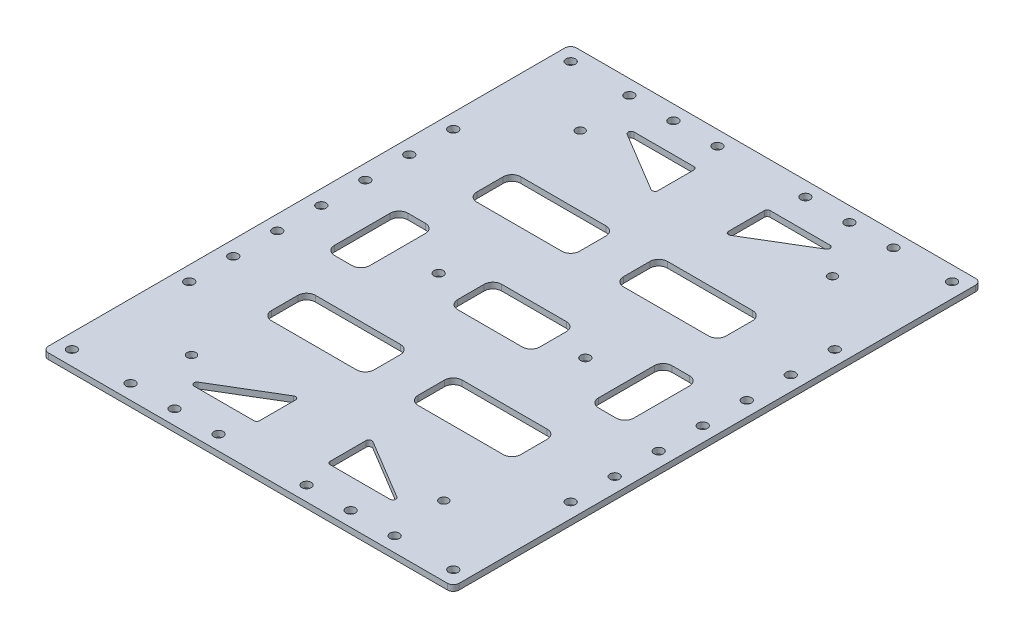
SolidWorks part; units mm, degrees
material "Thornel Mat VMA"
ref_plane "前视基准面" through (0, 0, 0) normal (0, 0, 1) x (1, 0, 0)
ref_plane "上视基准面" through (0, 0, 0) normal (0, 1, 0) x (1, 0, 0)
ref_plane "右视基准面" through (0, 0, 0) normal (1, 0, 0) x (0, 0, -1)
other "Configuration Table"
sketch "草图1" plane through (0, 0, 0) normal (0, 1, 0) x (1, 0, 0)
  line L1 (-90, -90) -> (90, -90)
  line L2 (-90, -90) -> (-90, 90)
  line L3 (-90, 90) -> (90, 90)
  line L4 (90, -90) -> (90, 90)
  line L5 (-90, -90) -> (90, 90) construction
  line L6 (-90, 90) -> (90, -90) construction
  point P0 (0, 0)
  dimension "D1" = 180
  dimension "D2" = 180
extrude "凸台-拉伸1" add sketch "草图1" along normal blind 2
sketch "草图2" plane through (0, 2, 0) normal (0, 1, 0) x (1, 0, 0)
  line L1 (-42.9895, -66.2305) -> (42.9895, -66.2305) construction
  line L2 (-42.9895, -66.2305) -> (-42.9895, 66.2305) construction
  line L3 (-42.9895, 66.2305) -> (42.9895, 66.2305) construction
  line L4 (42.9895, -66.2305) -> (42.9895, 66.2305) construction
  line L5 (-42.9895, -66.2305) -> (42.9895, 66.2305) construction
  line L6 (-42.9895, 66.2305) -> (42.9895, -66.2305) construction
  circle A0 centre (-42.9895, 66.2305) radius 1.5
  circle A1 centre (42.9895, 66.2305) radius 1.5
  circle A2 centre (-42.9895, -66.2305) radius 1.5
  circle A3 centre (42.9895, -66.2305) radius 1.5
  point P0 (0, 0)
  dimension "D3" = 3
  dimension "D1" = 132.461
  dimension "D2" = 85.979
extrude "切除-拉伸1" cut sketch "草图2" against normal blind 3
sketch "草图3" plane through (0, 2, 0) normal (0, 1, 0) x (1, 0, 0)
  line L0 (-90, 0) -> (90, 0) construction
  line L1 (-14, -7.5) -> (14, -7.5)
  line L2 (-14, -7.5) -> (-14, 7.5)
  line L3 (-14, 7.5) -> (14, 7.5)
  line L4 (14, -7.5) -> (14, 7.5)
  line L5 (-14, -7.5) -> (14, 7.5) construction
  line L6 (-14, 7.5) -> (14, -7.5) construction
  line L7 (-90, 90) -> (-90, -90) construction
  line L8 (90, -90) -> (90, 90) construction
  line L9 (0, 90) -> (0, -90) construction
  line L10 (90, 90) -> (-90, 90) construction
  line L11 (-90, -90) -> (90, -90) construction
  line L12 (-25, 35) -> (0, 35) construction
  line L13 (-42.5, 27.5) -> (-7.5, 27.5)
  line L14 (-42.5, 27.5) -> (-42.5, 42.5)
  line L15 (-42.5, 42.5) -> (-7.5, 42.5)
  line L16 (-7.5, 27.5) -> (-7.5, 42.5)
  line L17 (-42.5, 27.5) -> (-7.5, 42.5) construction
  line L18 (-42.5, 42.5) -> (-7.5, 27.5) construction
  line L23 (42.5, 42.5) -> (7.5, 42.5)
  line L24 (7.5, 27.5) -> (7.5, 42.5)
  line L25 (-25, 35) -> (-25, 0) construction
  line L26 (42.5, 27.5) -> (7.5, 27.5)
  line L27 (42.5, 27.5) -> (42.5, 42.5)
  line L28 (51, 12.5) -> (39, 12.5)
  line L29 (-51, -12.5) -> (-39, -12.5)
  line L30 (-51, -12.5) -> (-51, 12.5)
  line L31 (-51, 12.5) -> (-39, 12.5)
  line L32 (-39, -12.5) -> (-39, 12.5)
  line L33 (-51, -12.5) -> (-39, 12.5) construction
  line L34 (-51, 12.5) -> (-39, -12.5) construction
  line L35 (51, -12.5) -> (39, -12.5)
  line L36 (51, -12.5) -> (51, 12.5)
  line L37 (39, -12.5) -> (39, 12.5)
  line L38 (-42.5, -42.5) -> (-7.5, -42.5)
  line L39 (-7.5, -27.5) -> (-7.5, -42.5)
  line L40 (-42.5, -27.5) -> (-7.5, -27.5)
  line L41 (-42.5, -27.5) -> (-42.5, -42.5)
  line L42 (42.5, -27.5) -> (42.5, -42.5)
  line L43 (42.5, -27.5) -> (7.5, -27.5)
  line L44 (7.5, -27.5) -> (7.5, -42.5)
  line L45 (42.5, -42.5) -> (7.5, -42.5)
  line L51 (-37, 75) -> (-12, 75)
  line L52 (-12, 75) -> (-12, 60)
  line L56 (-12, 60) -> (-37, 75)
  line L57 (12, 75) -> (12, 60)
  line L58 (37, 75) -> (12, 75)
  line L59 (12, 60) -> (37, 75)
  line L60 (37, -75) -> (12, -75)
  line L61 (12, -60) -> (37, -75)
  line L62 (12, -75) -> (12, -60)
  line L63 (-12, -75) -> (-12, -60)
  line L64 (-37, -75) -> (-12, -75)
  line L65 (-12, -60) -> (-37, -75)
  point P0 (0, 0)
  point P18 (-25, 35)
  point P27 (-45, 0)
  dimension "D1" = 28
  dimension "D2" = 15
  dimension "D3" = 35
  dimension "D4" = 25
  dimension "D5" = 35
  dimension "D6" = 15
  dimension "D7" = 45
  dimension "D8" = 12
  dimension "D9" = 25
  dimension "D10" = 15
  dimension "D11" = 15
  dimension "D12" = 12
  dimension "D13" = 25
extrude "切除-拉伸2" cut sketch "草图3" against normal blind 3
fillet "圆角1" radius 3 4 edges at (-14, 1, 7.5) (14, 1, 7.5) (14, 1, -7.5) (-14, 1, -7.5)
sketch "草图5" plane through (0, 2, 0) normal (0, 1, 0) x (1, 0, 0)
  line L0 (80, 90) -> (90, 80)
  line L1 (-77.5, -77.5) -> (77.5, -77.5) construction
  line L2 (-77.5, -77.5) -> (-77.5, 77.5) construction
  line L3 (-77.5, 77.5) -> (77.5, 77.5) construction
  line L4 (77.5, -77.5) -> (77.5, 77.5) construction
  line L5 (-77.5, -77.5) -> (77.5, 77.5) construction
  line L6 (-77.5, 77.5) -> (77.5, -77.5) construction
  line L7 (69.0147, 77.5) -> (77.5, 69.0147) construction
  line L8 (69.0147, 77.5) -> (77.5, 85.9853) construction
  line L9 (77.5, 85.9853) -> (85.9853, 77.5) construction
  line L10 (77.5, 69.0147) -> (85.9853, 77.5) construction
  line L11 (69.0147, 77.5) -> (85.9853, 77.5) construction
  line L12 (77.5, 85.9853) -> (77.5, 69.0147) construction
  line L13 (90, 90) -> (-90, 90) construction
  line L14 (90, -90) -> (90, 90) construction
  line L24 (90, 80) -> (90, 90)
  line L25 (90, 90) -> (80, 90)
  line L26 (0, 90) -> (0, -90) construction
  line L27 (-90, -90) -> (90, -90) construction
  line L28 (90, 0) -> (-90, 0) construction
  line L29 (-90, 90) -> (-90, -90) construction
  line L30 (-77.5, 85.9853) -> (-77.5, 69.0147) construction
  line L31 (-69.0147, 77.5) -> (-85.9853, 77.5) construction
  line L32 (-77.5, 69.0147) -> (-85.9853, 77.5) construction
  line L33 (-77.5, 85.9853) -> (-85.9853, 77.5) construction
  line L34 (-69.0147, 77.5) -> (-77.5, 85.9853) construction
  line L35 (-69.0147, 77.5) -> (-77.5, 69.0147) construction
  line L36 (-90, 90) -> (-80, 90)
  line L37 (-90, 80) -> (-90, 90)
  line L38 (-80, 90) -> (-90, 80)
  line L39 (-69.0147, -77.5) -> (-77.5, -69.0147) construction
  line L40 (-69.0147, -77.5) -> (-77.5, -85.9853) construction
  line L41 (-77.5, -85.9853) -> (-85.9853, -77.5) construction
  line L42 (-77.5, -69.0147) -> (-85.9853, -77.5) construction
  line L43 (-69.0147, -77.5) -> (-85.9853, -77.5) construction
  line L44 (-77.5, -85.9853) -> (-77.5, -69.0147) construction
  line L45 (77.5, -85.9853) -> (77.5, -69.0147) construction
  line L46 (69.0147, -77.5) -> (85.9853, -77.5) construction
  line L47 (77.5, -69.0147) -> (85.9853, -77.5) construction
  line L48 (77.5, -85.9853) -> (85.9853, -77.5) construction
  line L49 (69.0147, -77.5) -> (77.5, -85.9853) construction
  line L50 (69.0147, -77.5) -> (77.5, -69.0147) construction
  line L51 (-80, -90) -> (-90, -80)
  line L52 (-90, -80) -> (-90, -90)
  line L53 (-90, -90) -> (-80, -90)
  line L54 (90, -90) -> (80, -90)
  line L55 (90, -80) -> (90, -90)
  line L56 (80, -90) -> (90, -80)
  circle A0 centre (69.0147, 77.5) radius 1.7 construction
  circle A1 centre (77.5, 69.0147) radius 1.7
  circle A2 centre (77.5, 85.9853) radius 1.7
  circle A3 centre (85.9853, 77.5) radius 1.7
  circle A4 centre (-85.9853, 77.5) radius 1.7
  circle A5 centre (-77.5, 85.9853) radius 1.7
  circle A6 centre (-77.5, 69.0147) radius 1.7 construction
  circle A7 centre (-69.0147, 77.5) radius 1.7 construction
  circle A8 centre (-69.0147, -77.5) radius 1.7 construction
  circle A9 centre (-77.5, -69.0147) radius 1.7 construction
  circle A10 centre (-77.5, -85.9853) radius 1.7
  circle A11 centre (-85.9853, -77.5) radius 1.7
  circle A12 centre (85.9853, -77.5) radius 1.7
  circle A13 centre (77.5, -85.9853) radius 1.7
  circle A14 centre (77.5, -69.0147) radius 1.7 construction
  circle A15 centre (69.0147, -77.5) radius 1.7 construction
  point P0 (0, 0)
  dimension "D3" = 3.4
  dimension "D1" = 12
  dimension "D2" = 12
  dimension "D4" = 155
  dimension "D5" = 10
  dimension "D6" = 10
extrude "切除-拉伸3" cut sketch "草图5" against normal through all
sketch "草图6" plane through (0, 2, 0) normal (0, 1, 0) x (1, 0, 0)
  line L0 (90, 70) -> (70, 50)
  line L1 (90, -80) -> (90, 80) construction
  line L2 (70, 50) -> (70, -50)
  line L3 (70, -50) -> (90, -70)
  line L4 (90, -70) -> (90, 70)
  line L5 (-90, 0) -> (90, 0) construction
  line L6 (-90, 80) -> (-90, -80) construction
  line L7 (0, 90) -> (0, -90) construction
  line L8 (80, 90) -> (-80, 90) construction
  line L9 (-80, -90) -> (80, -90) construction
  line L10 (-70, -50) -> (-90, -70)
  line L11 (-70, 50) -> (-70, -50)
  line L12 (-90, 70) -> (-70, 50)
  line L13 (-90, -70) -> (-90, 70)
  dimension "D1" = 140
  dimension "D2" = 20
  dimension "D3" = 20
  dimension "D4" = 20
extrude "切除-拉伸4" cut sketch "草图6" against normal blind 10
sketch "草图7" plane through (0, 0, 0) normal (0, -1, 0) x (1, 0, 0)
  line L0 (-70, 0) -> (70, 0) construction
  line L1 (-70, -50) -> (-70, 50) construction
  line L2 (70, 50) -> (70, -50) construction
  line L3 (0, 90) -> (0, -90) construction
  line L4 (-80, 90) -> (80, 90) construction
  line L5 (80, -90) -> (-80, -90) construction
  line L6 (-65, -15) -> (-65, 15) construction
  line L7 (-65, 15) -> (-65, 30) construction
  line L8 (-65, 30) -> (-65, 45) construction
  line L9 (0, 85) -> (-15, 85) construction
  line L10 (-15, 85) -> (-30, 85) construction
  line L11 (-30, 85) -> (-45, 85) construction
  line L12 (30, 85) -> (45, 85) construction
  line L13 (15, 85) -> (30, 85) construction
  line L14 (-65, -30) -> (-65, -45) construction
  line L15 (-65, -15) -> (-65, -30) construction
  line L16 (65, -15) -> (65, -30) construction
  line L17 (65, -30) -> (65, -45) construction
  line L18 (65, 30) -> (65, 45) construction
  line L19 (65, 15) -> (65, 30) construction
  line L20 (65, -15) -> (65, 15) construction
  line L21 (15, -85) -> (30, -85) construction
  line L22 (30, -85) -> (45, -85) construction
  line L23 (-30, -85) -> (-45, -85) construction
  line L24 (-15, -85) -> (-30, -85) construction
  line L25 (0, -85) -> (-15, -85) construction
  circle A0 centre (-65, 30) radius 1.6
  circle A1 centre (-65, 15) radius 1.6
  circle A2 centre (-65, 45) radius 1.6
  circle A3 centre (-45, 85) radius 1.6
  circle A4 centre (-30, 85) radius 1.6
  circle A5 centre (-15, 85) radius 1.6
  circle A6 centre (15, 85) radius 1.6
  circle A7 centre (30, 85) radius 1.6
  circle A8 centre (45, 85) radius 1.6
  circle A9 centre (-65, -45) radius 1.6
  circle A10 centre (-65, -15) radius 1.6
  circle A11 centre (-65, -30) radius 1.6
  circle A12 centre (65, -30) radius 1.6
  circle A13 centre (65, -15) radius 1.6
  circle A14 centre (65, -45) radius 1.6
  circle A15 centre (65, 45) radius 1.6
  circle A16 centre (65, 15) radius 1.6
  circle A17 centre (65, 30) radius 1.6
  circle A18 centre (45, -85) radius 1.6
  circle A19 centre (30, -85) radius 1.6
  circle A20 centre (15, -85) radius 1.6
  circle A21 centre (-15, -85) radius 1.6
  circle A22 centre (-30, -85) radius 1.6
  circle A23 centre (-45, -85) radius 1.6
  circle A24 centre (-65, 85) radius 1.6
  circle A25 centre (65, 85) radius 1.6
  circle A26 centre (65, -85) radius 1.6
  circle A27 centre (-65, -85) radius 1.6
  point P36 (-65, 0)
  point P51 (65, 0)
  dimension "D4" = 3.2
  dimension "D6" = 3.2
  dimension "D1" = 15
  dimension "D2" = 15
  dimension "D3" = 15
  dimension "D5" = 5
  dimension "D7" = 15
  dimension "D8" = 15
  dimension "D9" = 15
  dimension "D10" = 5
extrude "切除-拉伸5" cut sketch "草图7" against normal blind 10
fillet "圆角2" radius 3 40 edges at (80, 1, 90) (90, 1, 80) (90, 1, 70) (70, 1, 50) (-80, 1, 90) (-90, 1, 80) (-90, 1, 70) (-70, 1, 50) (-70, 1, -50) (-90, 1, -70) (-90, 1, -80) (-80, 1, -90) (80, 1, -90) (90, 1, -80) (90, 1, -70) (70, 1, -50) (-51, 1, -12.5) (-51, 1, 12.5) (-39, 1, 12.5) (-7.5, 1, -27.5) (-39, 1, -12.5) (-7.5, 1, -42.5) (-42.5, 1, -42.5) (-42.5, 1, -27.5) (-42.5, 1, 27.5) (-42.5, 1, 42.5) (-7.5, 1, 42.5) (-7.5, 1, 27.5) (7.5, 1, -42.5) (7.5, 1, -27.5) (42.5, 1, -27.5) (42.5, 1, -42.5) (7.5, 1, 42.5) (7.5, 1, 27.5) (42.5, 1, 42.5) (42.5, 1, 27.5) (39, 1, 12.5) (39, 1, -12.5) (51, 1, -12.5) (51, 1, 12.5)
fillet "圆角3" radius 1 12 edges at (-37, 1, 75) (-12, 1, 60) (-12, 1, 75) (12, 1, 60) (12, 1, 75) (37, 1, 75) (-37, 1, -75) (-12, 1, -60) (-12, 1, -75) (12, 1, -60) (37, 1, -75) (12, 1, -75)
sketch "草图8" plane through (0, 2, 0) normal (0, 1, 0) x (1, 0, 0)
  line L0 (-78.7574, -90) -> (78.7574, -90) construction
  line L1 (-70, 90) -> (70, 90)
  line L2 (-70, 90) -> (-70, -90)
  line L3 (-70, -90) -> (70, -90)
  line L4 (70, 90) -> (70, -90)
  line L5 (-70, 90) -> (70, -90) construction
  line L6 (-70, -90) -> (70, 90) construction
  line L7 (70, 48.7574) -> (70, -48.7574) construction
  line L8 (-25, 27.5) -> (-25, -27.5) construction
  line L9 (-39.5, 27.5) -> (-10.5, 27.5) construction
  line L10 (-10.5, -27.5) -> (-39.5, -27.5) construction
  line L11 (0, 90) -> (0, 0) construction
  line L12 (-65, 15) -> (-65, -15) construction
  line L24 (-78.7574, -90) -> (78.7574, -90)
  line L25 (80.8787, -89.1213) -> (89.1213, -80.8787)
  line L26 (90, -78.7574) -> (90, -71.2426)
  line L27 (89.1213, -69.1213) -> (70.8787, -50.8787)
  line L28 (70, -48.7574) -> (70, 48.7574)
  line L29 (70.8787, 50.8787) -> (89.1213, 69.1213)
  line L30 (90, 71.2426) -> (90, 78.7574)
  line L31 (89.1213, 80.8787) -> (80.8787, 89.1213)
  line L32 (78.7574, 90) -> (-78.7574, 90)
  line L33 (-80.8787, 89.1213) -> (-89.1213, 80.8787)
  line L34 (-90, 78.7574) -> (-90, 71.2426)
  line L35 (-89.1213, 69.1213) -> (-70.8787, 50.8787)
  line L36 (-70, 48.7574) -> (-70, -48.7574)
  line L37 (-70.8787, -50.8787) -> (-89.1213, -69.1213)
  line L38 (-90, -71.2426) -> (-90, -78.7574)
  line L39 (-89.1213, -80.8787) -> (-80.8787, -89.1213)
  line L40 (-78.7574, -90) -> (78.7574, -90)
  line L41 (80.8787, -89.1213) -> (89.1213, -80.8787)
  line L42 (90, -78.7574) -> (90, -71.2426)
  line L43 (89.1213, -69.1213) -> (70.8787, -50.8787)
  line L44 (70, -48.7574) -> (70, 48.7574)
  line L45 (70.8787, 50.8787) -> (89.1213, 69.1213)
  line L46 (90, 71.2426) -> (90, 78.7574)
  line L47 (89.1213, 80.8787) -> (80.8787, 89.1213)
  line L48 (78.7574, 90) -> (-78.7574, 90)
  line L49 (-80.8787, 89.1213) -> (-89.1213, 80.8787)
  line L50 (-90, 78.7574) -> (-90, 71.2426)
  line L51 (-89.1213, 69.1213) -> (-70.8787, 50.8787)
  line L52 (-70, 48.7574) -> (-70, -48.7574)
  line L53 (-70.8787, -50.8787) -> (-89.1213, -69.1213)
  line L54 (-90, -71.2426) -> (-90, -78.7574)
  line L55 (-89.1213, -80.8787) -> (-80.8787, -89.1213)
  circle A0 centre (-25, 0) radius 1.6
  circle A1 centre (-65, 0) radius 1.6
  circle A2 centre (25, 0) radius 1.6
  circle A3 centre (65, 0) radius 1.6
  arc A16 (78.7574, -90) -> (80.8787, -89.1213) centre (78.7574, -87) ccw
  arc A17 (89.1213, -80.8787) -> (90, -78.7574) centre (87, -78.7574) ccw
  arc A18 (90, -71.2426) -> (89.1213, -69.1213) centre (87, -71.2426) ccw
  arc A19 (70, -48.7574) -> (70.8787, -50.8787) centre (73, -48.7574) ccw
  arc A20 (70.8787, 50.8787) -> (70, 48.7574) centre (73, 48.7574) ccw
  arc A21 (89.1213, 69.1213) -> (90, 71.2426) centre (87, 71.2426) ccw
  arc A22 (90, 78.7574) -> (89.1213, 80.8787) centre (87, 78.7574) ccw
  arc A23 (80.8787, 89.1213) -> (78.7574, 90) centre (78.7574, 87) ccw
  arc A24 (-78.7574, 90) -> (-80.8787, 89.1213) centre (-78.7574, 87) ccw
  arc A25 (-89.1213, 80.8787) -> (-90, 78.7574) centre (-87, 78.7574) ccw
  arc A26 (-90, 71.2426) -> (-89.1213, 69.1213) centre (-87, 71.2426) ccw
  arc A27 (-70, 48.7574) -> (-70.8787, 50.8787) centre (-73, 48.7574) ccw
  arc A28 (-70.8787, -50.8787) -> (-70, -48.7574) centre (-73, -48.7574) ccw
  arc A29 (-89.1213, -69.1213) -> (-90, -71.2426) centre (-87, -71.2426) ccw
  arc A30 (-90, -78.7574) -> (-89.1213, -80.8787) centre (-87, -78.7574) ccw
  arc A31 (-80.8787, -89.1213) -> (-78.7574, -90) centre (-78.7574, -87) ccw
  arc A32 (78.7574, -90) -> (80.8787, -89.1213) centre (78.7574, -87) ccw
  arc A33 (89.1213, -80.8787) -> (90, -78.7574) centre (87, -78.7574) ccw
  arc A34 (90, -71.2426) -> (89.1213, -69.1213) centre (87, -71.2426) ccw
  arc A35 (70, -48.7574) -> (70.8787, -50.8787) centre (73, -48.7574) ccw
  arc A36 (70.8787, 50.8787) -> (70, 48.7574) centre (73, 48.7574) ccw
  arc A37 (89.1213, 69.1213) -> (90, 71.2426) centre (87, 71.2426) ccw
  arc A38 (90, 78.7574) -> (89.1213, 80.8787) centre (87, 78.7574) ccw
  arc A39 (80.8787, 89.1213) -> (78.7574, 90) centre (78.7574, 87) ccw
  arc A40 (-78.7574, 90) -> (-80.8787, 89.1213) centre (-78.7574, 87) ccw
  arc A41 (-89.1213, 80.8787) -> (-90, 78.7574) centre (-87, 78.7574) ccw
  arc A42 (-90, 71.2426) -> (-89.1213, 69.1213) centre (-87, 71.2426) ccw
  arc A43 (-70, 48.7574) -> (-70.8787, 50.8787) centre (-73, 48.7574) ccw
  arc A44 (-70.8787, -50.8787) -> (-70, -48.7574) centre (-73, -48.7574) ccw
  arc A45 (-89.1213, -69.1213) -> (-90, -71.2426) centre (-87, -71.2426) ccw
  arc A46 (-90, -78.7574) -> (-89.1213, -80.8787) centre (-87, -78.7574) ccw
  arc A47 (-80.8787, -89.1213) -> (-78.7574, -90) centre (-78.7574, -87) ccw
  point P0 (0, 0)
  dimension "D2" = 3.2
  dimension "D1" = 0
extrude "切除-拉伸6" cut sketch "草图8" against normal through all both and the other way through all contours A43 L2 L48 A40 L49 A41 L50 A42 L51 | L55 A47 L40 L2 A44 L53 A45 L54 A46 | A35 L4 L40 A32 L41 A33 L42 A34 L43 | L47 A39 L48 L4 A36 L45 A37 L46 A38 | A1 | A0 | A2 | A3
fillet "圆角4" radius 2 4 edges at (-70, 1, 90) (70, 1, 90) (70, 1, -90) (-70, 1, -90)
